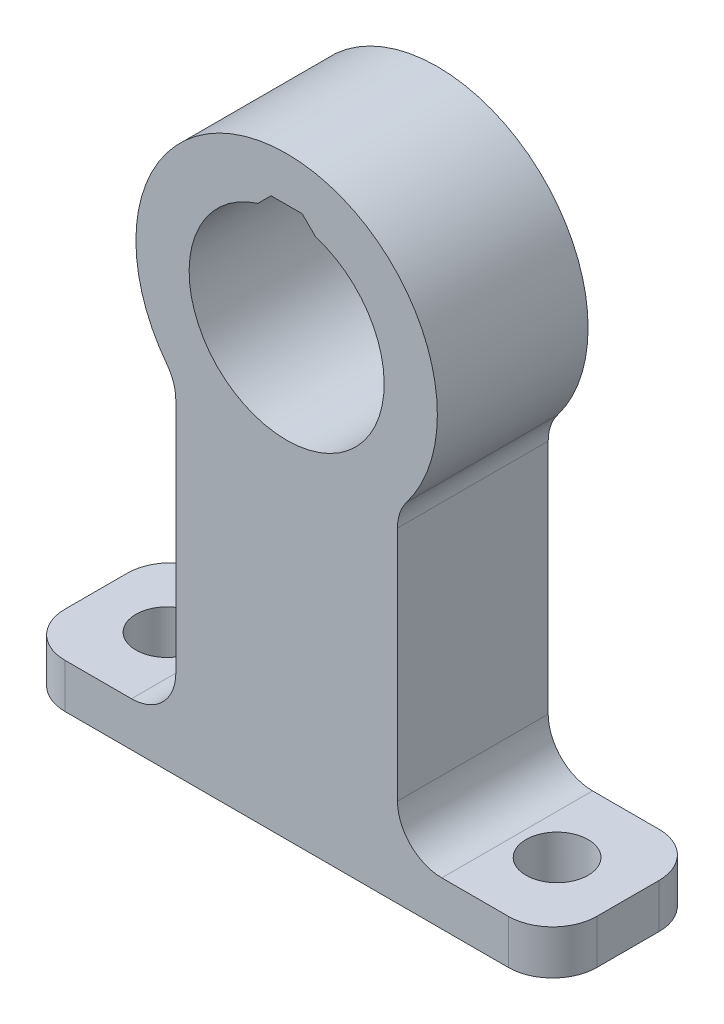
SolidWorks part; units mm, degrees
ref_plane "Front Plane" through (0, 0, 0) normal (0, 0, 1) x (1, 0, 0)
ref_plane "Top Plane" through (0, 0, 0) normal (0, 1, 0) x (1, 0, 0)
ref_plane "Right Plane" through (0, 0, 0) normal (1, 0, 0) x (0, 0, -1)
sketch "Sketch1" plane through (0, 0, 0) normal (0, 0, 1) x (1, 0, 0)
  line L0 (-12.5, -11.5217) -> (-12.5, -45)
  line L1 (12.5, -11.5217) -> (12.5, -45)
  line L8 (-3.25, 10.5089) -> (-1.7589, 12)
  line L9 (-1.7589, 12) -> (1.7589, 12)
  line L10 (1.7589, 12) -> (3.25, 10.5089)
  line L11 (12.5, -45) -> (30, -45)
  line L12 (30, -45) -> (30, -50)
  line L14 (30, -50) -> (-30, -50)
  line L15 (-30, -50) -> (-30, -45)
  line L16 (-30, -45) -> (-12.5, -45)
  arc A0 (-3.25, 10.5089) -> (3.25, 10.5089) centre (0, 0) ccw
  arc A1 (12.5, -11.5217) -> (-12.5, -11.5217) centre (0, 0) ccw
  point P8 (34.1884, -50)
  point P9 (0, 12)
  point P13 (12.5, -50.8165)
  point P18 (9.8762, -50.8165)
  dimension "D1" = 22
  dimension "D2" = 6
  dimension "D5" = 12
  dimension "D3" = 50
  dimension "D4" = 25
  dimension "D6" = 45
  dimension "D7" = 6.5
  dimension "D8" = 5
  dimension "D9" = 60
extrude "Boss-Extrude1" add sketch "Sketch1" along normal blind 17
sketch "Sketch2" plane through (0, -50, 0) normal (0, -1, 0) x (1, 0, 0)
  line L0 (0, 0) -> (0, 50000) construction
  line L1 (-30, 0) -> (30, 0) construction
  line L2 (-30, 17) -> (-30, 0) construction
  line L3 (-30, 8.5) -> (-22, 8.5) construction
  circle A0 centre (-22, 8.5) radius 3.5
  circle A1 centre (22, 8.5) radius 3.5
  point P6 (0, 0)
  point P7 (-30, 8.5)
  dimension "D1" = 7
  dimension "D2" = 44
extrude "Cut-Extrude1" cut sketch "Sketch2" against normal up to next
fillet "Fillet1" radius 5 8 edges at (12.5, -11.5217, 8.5) (-12.5, -11.5217, 8.5) (-12.5, -45, 8.5) (-30, -47.5, 0) (12.5, -45, 8.5) (30, -47.5, 0) (30, -47.5, 17) (-30, -47.5, 17)
